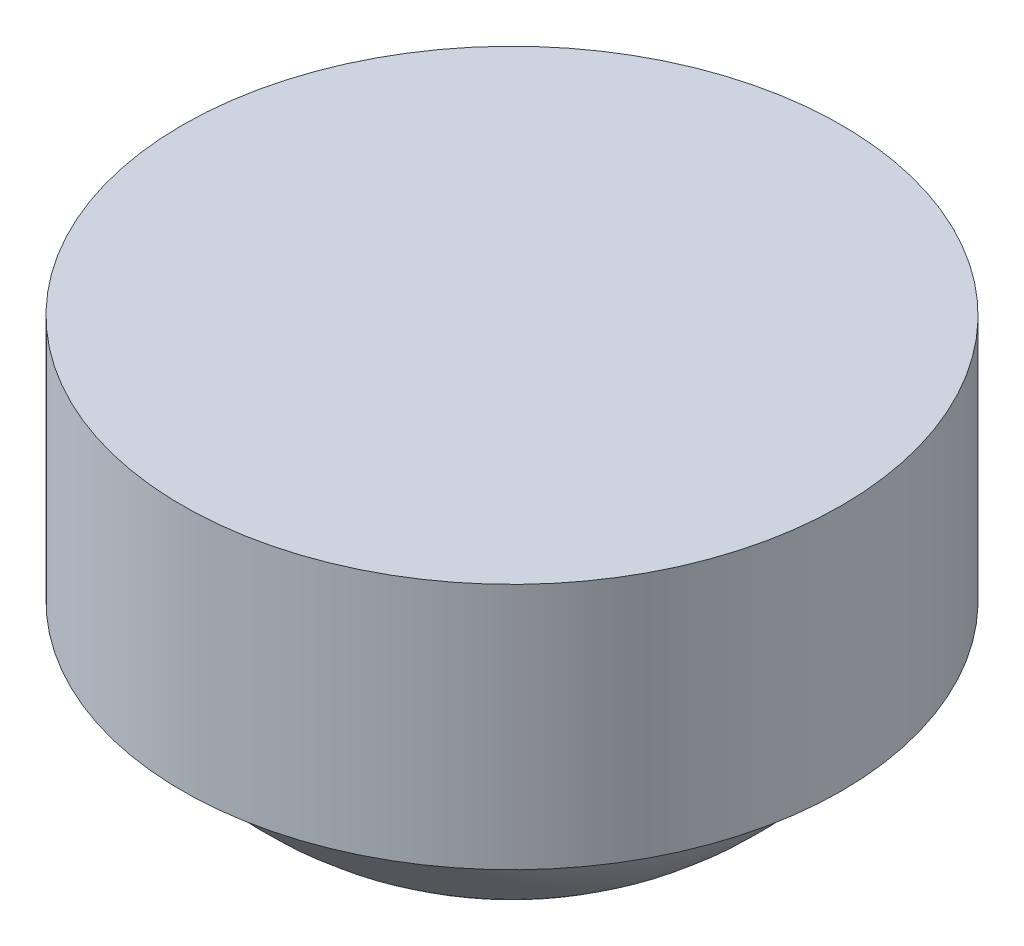
SolidWorks part; units mm, degrees
ref_plane "Front Plane" through (0, 0, 0) normal (0, 0, 1) x (1, 0, 0)
ref_plane "Top Plane" through (0, 0, 0) normal (0, 1, 0) x (1, 0, 0)
ref_plane "Right Plane" through (0, 0, 0) normal (1, 0, 0) x (0, 0, -1)
sketch "Sketch1" plane through (0, 0, 0) normal (0, 0, 1) x (1, 0, 0)
  line L0 (20, -67) -> (0, -67)
  line L1 (0, -67) -> (0, -93)
  line L2 (18.4662, -82) -> (20, -82)
  line L3 (20, -82) -> (20, -67)
  line L4 (0, -67) -> (0, -93) construction
  arc A0 (0, -93) -> (18.4662, -82) centre (0, -72) ccw
  dimension "D3" = 21
  dimension "D1" = 20
  dimension "D2" = 26
  dimension "D4" = 15
revolve "Revolve1" add sketch "Sketch1" angle 360 about L4
